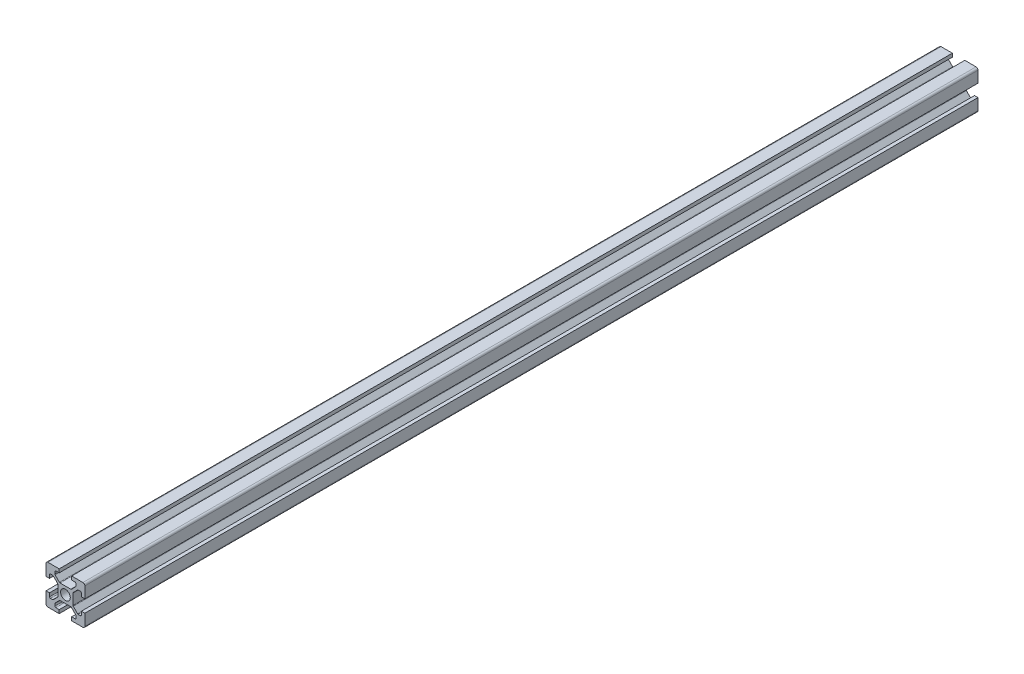
SolidWorks part; units mm, degrees
material "1060 Alloy"
ref_plane "Front Plane" through (0, 0, 0) normal (0, 0, 1) x (1, 0, 0)
ref_plane "Top Plane" through (0, 0, 0) normal (0, 1, 0) x (1, 0, 0)
ref_plane "Right Plane" through (0, 0, 0) normal (1, 0, 0) x (0, 0, -1)
sketch "Sketch1" plane through (0, 0, 0) normal (0, 0, 1) x (1, 0, 0)
  line L0 (20, 0) -> (-8.059, 28.059) construction
  line L1 (0, 0) -> (6.8, 0)
  line L2 (0, 0) -> (0, 6.8)
  line L3 (0, 20) -> (6.8, 20)
  line L4 (20, 0) -> (20, 6.8)
  line L5 (6.8, 20) -> (6.8, 18.2)
  line L6 (20, 20) -> (8.2322, 8.2322) construction
  line L7 (12.95, 6.1) -> (7.05, 6.1)
  line L8 (13.9, 7.05) -> (13.9, 12.95)
  line L9 (12.95, 13.9) -> (7.05, 13.9)
  line L10 (6.1, 7.05) -> (6.1, 12.95)
  line L11 (13.9, 6.1) -> (6.1, 13.9) construction
  line L12 (13.9, 13.9) -> (6.1, 6.1) construction
  line L13 (4.55, 16.4) -> (7.05, 13.9)
  line L14 (13.2, 18.2) -> (13.2, 20)
  line L15 (1.8, 6.8) -> (0, 6.8)
  line L16 (0, 13.2) -> (0, 20)
  line L17 (0, 13.2) -> (1.8, 13.2)
  line L18 (10, 10) -> (10, 13.9) construction
  line L19 (16.4, 4.55) -> (13.9, 7.05)
  line L20 (4.55, 16.4) -> (4.55, 18.2)
  line L21 (4.55, 18.2) -> (6.8, 18.2)
  line L22 (13.2, 18.2) -> (15.45, 18.2)
  line L23 (15.45, 18.2) -> (15.45, 16.4)
  line L24 (15.45, 16.4) -> (12.95, 13.9)
  line L25 (16.4, 4.55) -> (18.2, 4.55)
  line L26 (18.2, 4.55) -> (18.2, 6.8)
  line L27 (20, 6.8) -> (18.2, 6.8)
  line L28 (18.2, 13.2) -> (20, 13.2)
  line L29 (18.2, 13.2) -> (18.2, 15.45)
  line L30 (18.2, 15.45) -> (16.4, 15.45)
  line L31 (16.4, 15.45) -> (13.9, 12.95)
  line L32 (1.8, 4.55) -> (3.6, 4.55)
  line L33 (3.6, 15.45) -> (6.1, 12.95)
  line L34 (3.6, 15.45) -> (1.8, 15.45)
  line L35 (1.8, 15.45) -> (1.8, 13.2)
  line L36 (0, 13.2) -> (1.8, 13.2)
  line L37 (1.8, 6.8) -> (0, 6.8)
  line L38 (3.6, 4.55) -> (6.1, 7.05)
  line L39 (1.8, 6.8) -> (1.8, 4.55)
  line L40 (15.45, 3.6) -> (12.95, 6.1)
  line L41 (4.55, 3.6) -> (7.05, 6.1)
  line L42 (4.55, 1.8) -> (4.55, 3.6)
  line L43 (6.8, 1.8) -> (4.55, 1.8)
  line L44 (6.8, 1.8) -> (6.8, 0)
  line L45 (15.45, 3.6) -> (15.45, 1.8)
  line L46 (15.45, 1.8) -> (13.2, 1.8)
  line L47 (13.2, 0) -> (13.2, 1.8)
  line L48 (13.2, 20) -> (20, 20)
  line L49 (20, 13.2) -> (20, 20)
  line L50 (13.2, 0) -> (20, 0)
  line L51 (6.1, 6.1) -> (-5.5045, -5.5045) construction
  circle A0 centre (10, 10) radius 2.5
  point P25 (10, 16.4)
  point P39 (13.2, 19.1)
  point P46 (0.9, 6.8)
  dimension "D3" = 5
  dimension "D2" = 20
  dimension "D4" = 7.8
  dimension "D5" = 7.8
  dimension "D6" = 6.8
  dimension "D7" = 6.8
  dimension "D8" = 1.8
  dimension "D9" = 10.9
  dimension "D10" = 1.8
  dimension "D11" = 10.9
  dimension "D12" = 20
extrude "Boss-Extrude1" add sketch "Sketch1" along normal mid plane 460 contours L47 L50 L4 L27 L26 L25 L19 L8 L31 L30 L29 L28 L49 L48 L14 L22 L23 L24 L9 L13 L20 L21 L5 L3 L16 L17 L35 L34 L33 L10 L38 L32 L39 L15 L2 L1 L44 L43 L42 L41 L7 L40 L45 L46 A0
fillet "Fillet1" radius 1 4 edges at (20, 20, 0) (20, 0, 0) (0, 0, 0) (0, 20, 0)
fillet "Fillet2" radius 0.5 6 edges at (4.55, 18.2, 0) (4.55, 16.4, 0) (7.05, 13.9, 0) (15.45, 18.2, 0) (15.45, 16.4, 0) (12.95, 13.9, 0)
fillet "Fillet3" radius 0.5 6 edges at (18.2, 15.45, 0) (16.4, 15.45, 0) (13.9, 12.95, 0) (18.2, 4.55, 0) (13.9, 7.05, 0) (16.4, 4.55, 0)
fillet "Fillet4" radius 0.5 6 edges at (1.8, 15.45, 0) (3.6, 15.45, 0) (6.1, 12.95, 0) (3.6, 4.55, 0) (1.8, 4.55, 0) (6.1, 7.05, 0)
fillet "Fillet5" radius 0.5 6 edges at (7.05, 6.1, 0) (4.55, 3.6, 0) (4.55, 1.8, 0) (15.45, 1.8, 0) (15.45, 3.6, 0) (12.95, 6.1, 0)
